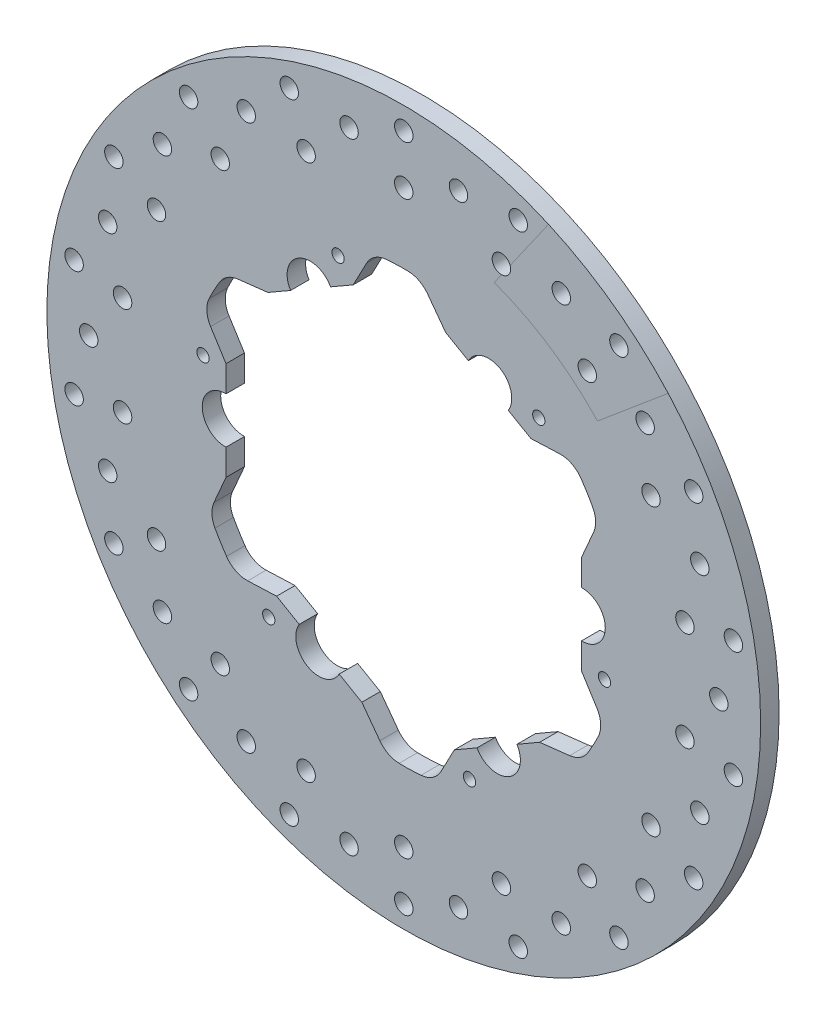
SolidWorks part; units mm, degrees
material "Gray Cast Iron"
ref_plane "Front Plane" through (0, 0, 0) normal (0, 0, 1) x (1, 0, 0)
ref_plane "Top Plane" through (0, 0, 0) normal (0, 1, 0) x (1, 0, 0)
ref_plane "Right Plane" through (0, 0, 0) normal (1, 0, 0) x (0, 0, -1)
sketch "Sketch1" plane through (0, 0, 0) normal (0, 0, 1) x (1, 0, 0)
  line L0 (-55.5625, 0) -> (-55.5625, -25.0191) construction
  line L1 (-45.8597, 11.4094) -> (-45.8597, 4.6599)
  line L2 (-45.8597, 11.4094) -> (-51.6236, 20.5474)
  line L3 (-45.8597, -13.9906) -> (-50.1583, -23.9026)
  line L4 (-45.8597, -7.2411) -> (-45.8597, -13.9906)
  line L5 (-13.049, 45.4204) -> (-8.0172, 54.981)
  line L6 (-13.049, 45.4204) -> (-18.8943, 42.0456)
  line L7 (-29.2008, 36.0951) -> (-35.0461, 32.7204)
  line L8 (-35.0461, 32.7204) -> (-45.7794, 31.4871)
  line L9 (32.8107, 34.011) -> (43.6064, 34.4336)
  line L10 (32.8107, 34.011) -> (26.9654, 37.3857)
  line L11 (16.6589, 43.3362) -> (10.8136, 46.711)
  line L12 (10.8136, 46.711) -> (4.3789, 55.3897)
  line L13 (45.8597, -11.4094) -> (51.6236, -20.5474)
  line L14 (45.8597, -11.4094) -> (45.8597, -4.6599)
  line L15 (45.8597, 7.2411) -> (45.8597, 13.9906)
  line L16 (45.8597, 13.9906) -> (50.1583, 23.9026)
  line L17 (13.049, -45.4204) -> (8.0172, -54.981)
  line L18 (13.049, -45.4204) -> (18.8943, -42.0456)
  line L19 (29.2008, -36.0951) -> (35.0461, -32.7204)
  line L20 (35.0461, -32.7204) -> (45.7794, -31.4871)
  line L21 (-32.8107, -34.011) -> (-43.6064, -34.4336)
  line L22 (-32.8107, -34.011) -> (-26.9654, -37.3857)
  line L23 (-16.6589, -43.3362) -> (-10.8136, -46.711)
  line L24 (-10.8136, -46.711) -> (-4.3789, -55.3897)
  circle A0 centre (0, 0) radius 92.075
  arc A1 (-45.7794, 31.4871) -> (-51.6236, 20.5474) centre (0, 0) ccw
  arc A3 (-45.8597, 4.6599) -> (-45.8597, -7.2411) centre (-46.0375, -1.2906) ccw
  arc A4 (-18.8943, 42.0456) -> (-29.2008, 36.0951) centre (-24.1364, 39.2243) ccw
  arc A5 (26.9654, 37.3857) -> (16.6589, 43.3362) centre (21.9011, 40.5149) ccw
  arc A6 (45.8597, -4.6599) -> (45.8597, 7.2411) centre (46.0375, 1.2906) ccw
  arc A7 (18.8943, -42.0456) -> (29.2008, -36.0951) centre (24.1364, -39.2243) ccw
  arc A8 (-26.9654, -37.3857) -> (-16.6589, -43.3362) centre (-21.9011, -40.5149) ccw
  arc A9 (4.3789, 55.3897) -> (-8.0172, 54.981) centre (0, 0) ccw
  arc A10 (50.1583, 23.9026) -> (43.6064, 34.4336) centre (0, 0) ccw
  arc A11 (45.7794, -31.4871) -> (51.6236, -20.5474) centre (0, 0) ccw
  arc A12 (-4.3789, -55.3897) -> (8.0172, -54.981) centre (0, 0) ccw
  arc A13 (-55.5625, 0) -> (-43.6064, -34.4336) centre (0, 0) ccw
  point P50 (0, 0)
  dimension "D1" = 184.15
  dimension "D2" = 111.125
  dimension "D3" = 11.9062
  dimension "D4" = 9.525
  dimension "D5" = 0.1778
  dimension "D6" = 25.4
  dimension "D7" = 44.45
  dimension "D9" = 47.2577
  dimension "D8" = 6
extrude "Boss-Extrude1" add sketch "Sketch1" along normal blind 4.7625
fillet "Fillet1" radius 6.35 12 edges at (8.0172, -54.981, 2.3813) (45.7794, -31.4871, 2.3813) (-4.3789, -55.3897, 2.3813) (-43.6064, -34.4336, 2.3813) (51.6236, -20.5474, 2.3813) (50.1583, 23.9026, 2.3813) (43.6064, 34.4336, 2.3813) (4.3789, 55.3897, 2.3813) (-50.1583, -23.9026, 2.3813) (-51.6236, 20.5474, 2.3813) (-8.0172, 54.981, 2.3813) (-45.7794, 31.4871, 2.3813)
sketch "Sketch4" plane through (0, 0, 4.7625) normal (0, 0, 1) x (1, 0, 0)
  circle A0 centre (-16.953, 50.0113) radius 1.5875
  arc A1 (-18.8943, 42.0456) -> (-29.2008, 36.0951) centre (-24.1364, 39.2243) ccw construction
  circle A3 centre (34.8346, 39.6874) radius 1.5875
  circle A4 centre (51.7876, -10.3239) radius 1.5875
  circle A5 centre (16.953, -50.0113) radius 1.5875
  circle A6 centre (-34.8346, -39.6874) radius 1.5875
  circle A7 centre (-51.7876, 10.3239) radius 1.5875
  point P6 (-27.113, 44.3799)
  point P23 (0, 0)
  dimension "D1" = 52.8066
  dimension "D2" = 3.175
  dimension "D3" = 10.16
  dimension "D4" = 6
extrude "Cut-Extrude1" cut sketch "Sketch4" against normal through all
sketch "Sketch5" plane through (0, 0, 4.7625) normal (0, 0, 1) x (1, 0, 0)
  line L0 (0, 120.6115) -> (0, 84.6416) construction
  line L1 (-74.0774, 0) -> (83.9652, 0) construction
  line L2 (0, 0) -> (20.7529, 117.6956) construction
  circle A0 centre (0, 0) radius 68.58 construction
  circle A4 centre (0, 86.36) radius 2.3812
  circle A5 centre (0, 73.66) radius 2.3812
  circle A6 centre (14.1141, 80.0452) radius 2.3812
  point P13 (0, 0)
  dimension "D1" = 137.16
  dimension "D2" = 4.7625
  dimension "D3" = 12.7
  dimension "D4" = 86.36
  dimension "D5" = 10
  dimension "D6" = 81.28
extrude "Cut-Extrude2" cut sketch "Sketch5" against normal through all
sketch "Sketch6" plane through (0, 0, 4.7625) normal (0, 0, 1) x (1, 0, 0)
  line L0 (0, 0) -> (0, 110.5188) construction
  line L1 (0, 0) -> (38.9978, 107.1456) construction
  line L4 (23.3472, 64.1458) -> (37.3582, 84.1556)
  line L5 (49.9701, 46.5054) -> (68.2294, 61.8268)
  arc A2 (68.2294, 61.8268) -> (37.3582, 84.1556) centre (0, 0) ccw
  arc A3 (49.9701, 46.5054) -> (23.3472, 64.1458) centre (0, 0) ccw
  dimension "D2" = 15
  dimension "D3" = 184.15
  dimension "D6" = 136.525
  dimension "D1" = 20
  dimension "D4" = 15
  dimension "D5" = 38.1
split line "Split Line1"
pattern_circular "FrontPaternCopy" count 18 over 360 about axis through (0, 0, 0) along (0, 0, 1) of "Cut-Extrude2"
equation "\"holenumber\"=18"
equation "\"D1@FrontPaternCopy\"=\"holenumber\""
